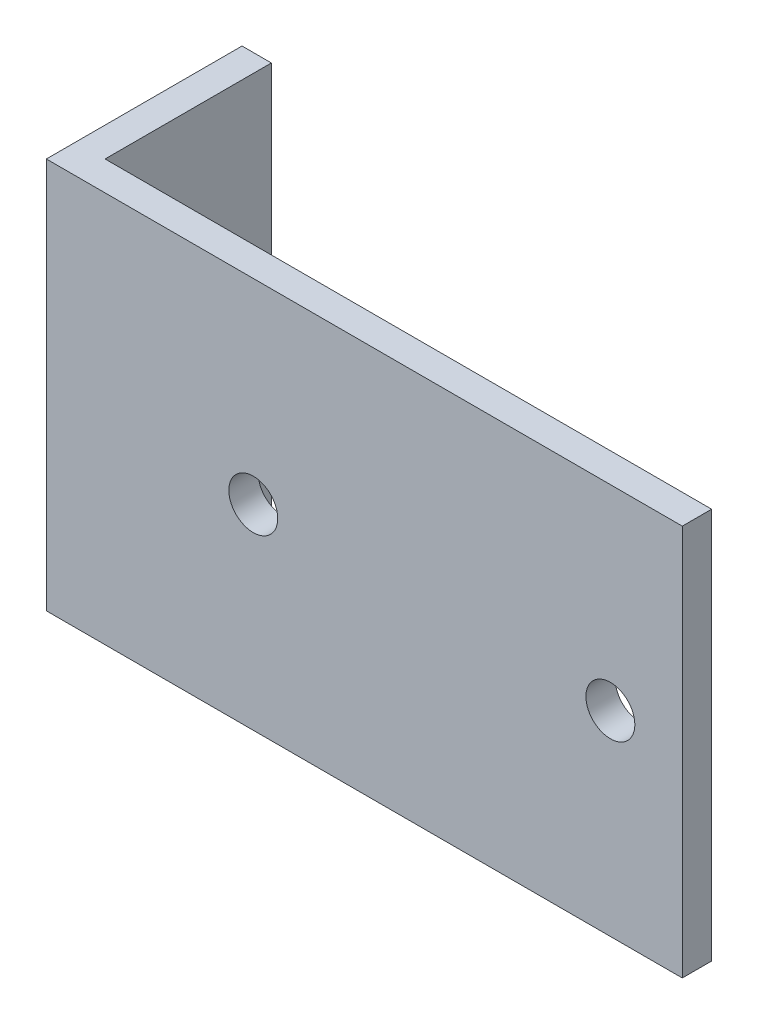
SolidWorks part; units mm, degrees
ref_plane "Front Plane" through (0, 0, 0) normal (0, 0, 1) x (1, 0, 0)
ref_plane "Top Plane" through (0, 0, 0) normal (0, 1, 0) x (1, 0, 0)
ref_plane "Right Plane" through (0, 0, 0) normal (1, 0, 0) x (0, 0, -1)
sketch "Sketch1" plane through (0, 0, 0) normal (0, 1, 0) x (1, 0, 0)
  line L0 (0, 0) -> (0, 20)
  line L1 (0, 20) -> (3, 20)
  line L2 (3, 20) -> (3, 3)
  line L3 (3, 3) -> (65, 3)
  line L4 (65, 3) -> (65, 0)
  line L5 (65, 0) -> (0, 0)
  dimension "D1" = 3
  dimension "D2" = 3
  dimension "D3" = 65
  dimension "D4" = 20
extrude "Boss-Extrude1" add sketch "Sketch1" along normal blind 40
sketch "Sketch2" plane through (0, 0, 0) normal (0, 0, 1) x (1, 0, 0)
  line L0 (0, 20) -> (65, 20) construction
  line L1 (0, 40) -> (0, 0) construction
  line L2 (65, 40) -> (65, 0) construction
  circle A0 centre (21.15, 20) radius 2.5
  circle A1 centre (57.65, 20) radius 2.5
  dimension "D1" = 21.15
  dimension "D2" = 5
  dimension "D3" = 5
  dimension "D4" = 36.5
extrude "Cut-Extrude1" cut sketch "Sketch2" against normal through all
